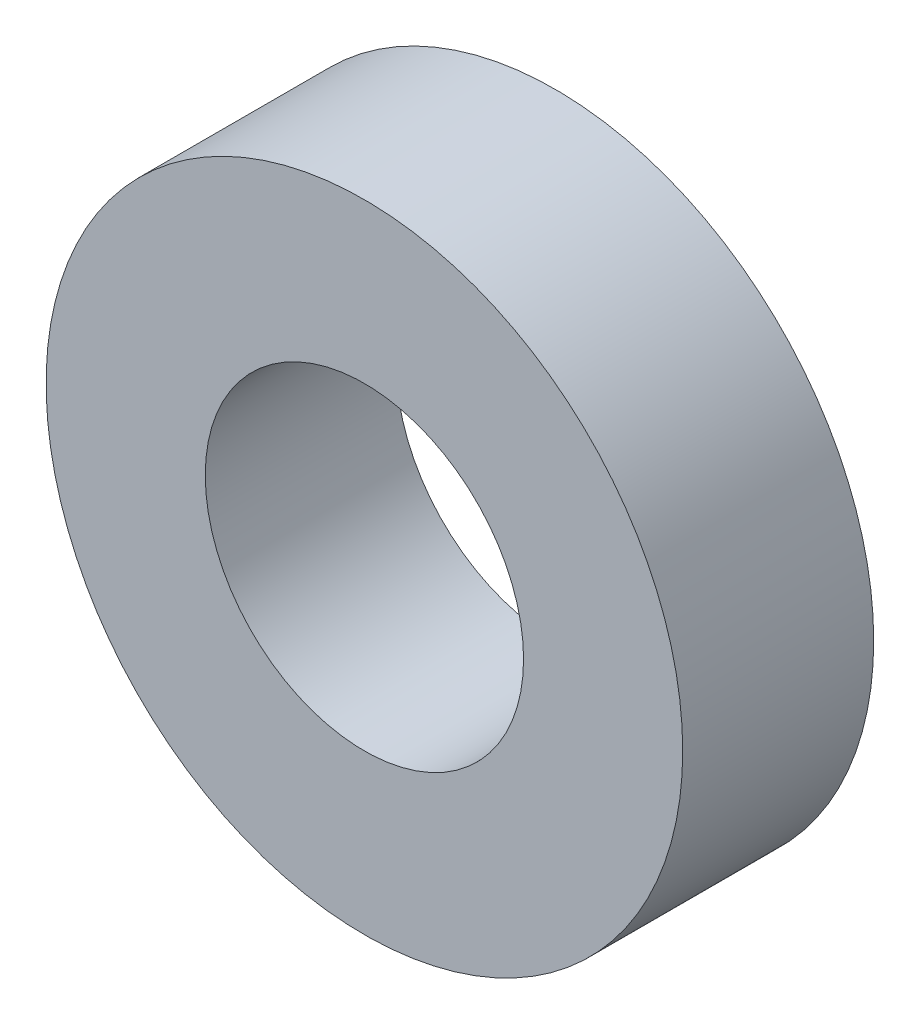
SolidWorks part; units mm, degrees
ref_plane "Front Plane" through (0, 0, 0) normal (0, 0, 1) x (1, 0, 0)
ref_plane "Top Plane" through (0, 0, 0) normal (0, 1, 0) x (1, 0, 0)
ref_plane "Right Plane" through (0, 0, 0) normal (1, 0, 0) x (0, 0, -1)
sketch "Sketch1" plane through (0, 0, 0) normal (0, 0, 1) x (1, 0, 0)
  circle A0 centre (0, 0) radius 5
  circle A1 centre (0, 0) radius 2.5
  dimension "D1" = 10
  dimension "D2" = 5
extrude "Boss-Extrude1" add sketch "Sketch1" along normal blind 3
